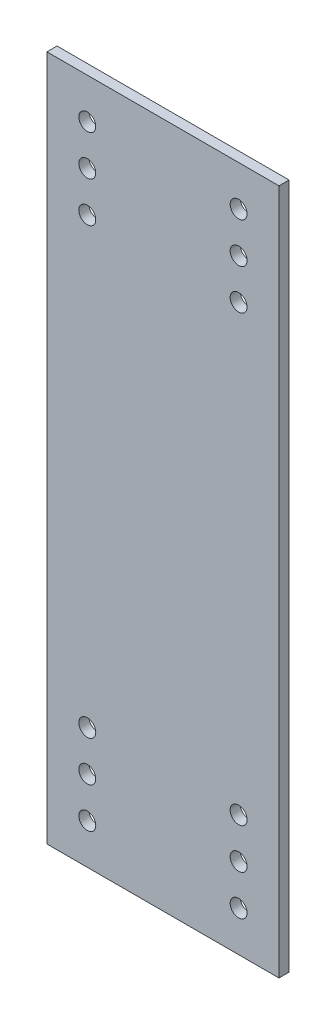
SolidWorks part; units mm, degrees
ref_plane "Front Plane" through (0, 0, 0) normal (0, 0, 1) x (1, 0, 0)
ref_plane "Top Plane" through (0, 0, 0) normal (0, 1, 0) x (1, 0, 0)
ref_plane "Right Plane" through (0, 0, 0) normal (1, 0, 0) x (0, 0, -1)
sketch "Sketch1" plane through (0, 0, 0) normal (0, 0, 1) x (1, 0, 0)
  line L1 (-36.5125, 107.95) -> (36.5125, 107.95)
  line L2 (-36.5125, 107.95) -> (-36.5125, -107.95)
  line L3 (-36.5125, -107.95) -> (36.5125, -107.95)
  line L4 (36.5125, 107.95) -> (36.5125, -107.95)
  line L5 (-36.5125, 107.95) -> (36.5125, -107.95) construction
  line L6 (-36.5125, -107.95) -> (36.5125, 107.95) construction
  point P0 (0, 0)
  dimension "D1" = 73.025
  dimension "D2" = 215.9
extrude "Boss-Extrude1" add sketch "Sketch1" along normal blind 3.175
sketch "Sketch2" plane through (0, 0, 3.175) normal (0, 0, 1) x (1, 0, 0)
  line L0 (-36.5125, -107.95) -> (-23.8125, -107.95) construction
  line L1 (-36.5125, -107.95) -> (36.5125, -107.95) construction
  line L2 (-23.8125, -107.95) -> (-23.8125, -95.25) construction
  line L3 (-23.8125, -95.25) -> (-23.8125, -82.55) construction
  line L4 (-23.8125, -82.55) -> (-23.8125, -69.85) construction
  line L5 (0, -107.95) -> (0, 107.95) construction
  line L6 (36.5125, 107.95) -> (-36.5125, 107.95) construction
  line L7 (-36.5125, 0) -> (36.5125, 0) construction
  line L8 (-36.5125, 107.95) -> (-36.5125, -107.95) construction
  line L9 (36.5125, -107.95) -> (36.5125, 107.95) construction
  circle A0 centre (-23.8125, -69.85) radius 2.667
  circle A1 centre (-23.8125, -82.55) radius 2.667
  circle A2 centre (-23.8125, -95.25) radius 2.667
  circle A3 centre (-23.8125, 95.25) radius 2.667
  circle A4 centre (-23.8125, 82.55) radius 2.667
  circle A5 centre (-23.8125, 69.85) radius 2.667
  circle A6 centre (23.8125, 95.25) radius 2.667
  circle A7 centre (23.8125, 82.55) radius 2.667
  circle A8 centre (23.8125, 69.85) radius 2.667
  circle A9 centre (23.8125, -95.25) radius 2.667
  circle A10 centre (23.8125, -82.55) radius 2.667
  circle A11 centre (23.8125, -69.85) radius 2.667
  point P39 (0, 0)
  dimension "D1" = 12.7
extrude "Cut-Extrude1" cut sketch "Sketch2" against normal blind 3.175
